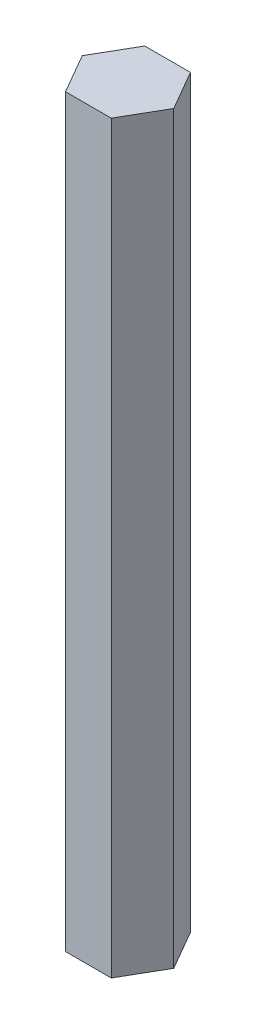
SolidWorks part; units mm, degrees
ref_plane "Front Plane" through (0, 0, 0) normal (0, 0, 1) x (1, 0, 0)
ref_plane "Top Plane" through (0, 0, 0) normal (0, 1, 0) x (1, 0, 0)
ref_plane "Right Plane" through (0, 0, 0) normal (1, 0, 0) x (0, 0, -1)
sketch "Sketch1" plane through (0, 0, 0) normal (0, 1, 0) x (1, 0, 0)
  line L1 (1.4434, 2.5) -> (-1.4434, 2.5)
  line L2 (-1.4434, 2.5) -> (-2.8868, 0)
  line L3 (-2.8868, 0) -> (-1.4434, -2.5)
  line L4 (-1.4434, -2.5) -> (1.4434, -2.5)
  line L5 (1.4434, -2.5) -> (2.8868, 0)
  line L6 (2.8868, 0) -> (1.4434, 2.5)
  circle A0 centre (0, 0) radius 2.5 construction
  dimension "D1" = 5
extrude "Boss-Extrude1" add sketch "Sketch1" along normal blind 47
